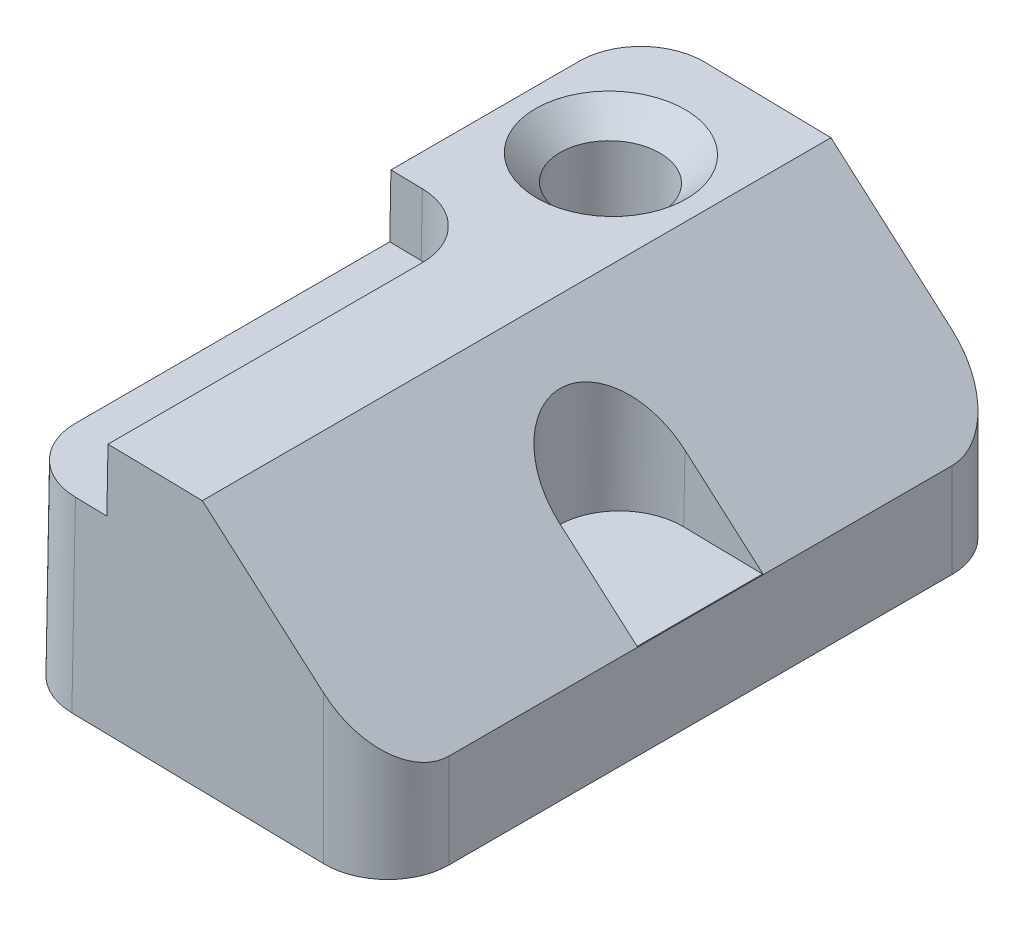
SolidWorks part; units mm, degrees
material "Plain Carbon Steel"
ref_plane "Front Plane" through (0, 0, 0) normal (0, 0, 1) x (1, 0, 0)
ref_plane "Top Plane" through (0, 0, 0) normal (0, 1, 0) x (1, 0, 0)
ref_plane "Right Plane" through (0, 0, 0) normal (1, 0, 0) x (0, 0, -1)
sketch "Sketch1" plane through (0, 0, 0) normal (0, 0, 1) x (1, 0, 0)
  line L0 (0, 0) -> (0.9549, 50.8)
  line L1 (0.9549, 50.8) -> (39.0549, 50.0838)
  line L2 (39.0549, 50.0838) -> (76.2, 17.6177)
  line L3 (76.2, 17.6177) -> (76.2, -1.4323)
  line L4 (76.2, -1.4323) -> (0, 0)
  dimension "D1" = 38.1
  dimension "D2" = 19.05
  dimension "D3" = 76.2
  dimension "D4" = 50.8
extrude "Boss-Extrude1" add sketch "Sketch1" along normal blind 127
sketch "Sketch2" plane through (0.9549, 50.8, 0) normal (0.0188, 0.9998, 0) x (0.9998, -0.0188, 0)
  line L0 (38.1067, 0) -> (0, 0) construction
  line L1 (0, -127) -> (0, 0) construction
  circle A0 centre (19.05, -25.4) radius 10.16
  dimension "D1" = 20.32
  dimension "D2" = 25.4
  dimension "D3" = 19.05
extrude "Cut-Extrude1" cut sketch "Sketch2" against normal through all
chamfer "Chamfer1" distance 5.08 angle 45 1 edges at (9.8433, 50.6329, 25.4)
sketch "Sketch3" plane through (0.9549, 50.8, 0) normal (0.0188, 0.9998, 0) x (0.9998, -0.0188, 0)
  line L1 (0, -127) -> (19.05, -127)
  line L2 (0, -127) -> (0, -50.8)
  line L3 (0, -50.8) -> (19.05, -50.8)
  line L4 (19.05, -127) -> (19.05, -50.8)
  dimension "D1" = 19.05
  dimension "D2" = 76.2
extrude "Cut-Extrude2" cut sketch "Sketch3" against normal blind 12.7
fillet "Fillet1" radius 12.7 1 edges at (19.8822, 44.0931, 50.8)
sketch "Sketch9" plane through (41.7308, 47.745, 0) normal (0.6581, 0.7529, 0) x (0.7529, -0.6581, 0)
  line L0 (45.7797, -63.5) -> (-76.9383, -63.5) construction
  line L1 (45.7797, -127) -> (45.7797, 0) construction
  point P4 (0, 0)
sketch "Sketch10" plane through (0.9549, 50.8, 0) normal (0.0188, 0.9998, 0) x (0.9998, -0.0188, 0)
  line L0 (75.7554, -50.8) -> (59.7534, -50.8)
  line L1 (59.7534, -76.2) -> (75.7554, -76.2)
  line L2 (75.7554, -76.2) -> (75.7554, -50.8)
  line L3 (75.8554, -63.5) -> (-18.0449, -63.5) construction
  arc A0 (59.7534, -50.8) -> (59.7534, -76.2) centre (59.7534, -63.5) ccw
  point P4 (0, 0)
  dimension "D2" = 12.7
  dimension "D1" = 16.002
extrude "Cut-Extrude4" cut sketch "Sketch10" against normal up to vertex (31.7623 mm away) contours L2 L0 A0 L1
fillet "Fillet2" radius 12.7 1 edges at (76.2, 8.0927, 127)
fillet "Fillet3" radius 12.7 1 edges at (0.3581, 19.0511, 127)
fillet "Fillet4" radius 12.7 1 edges at (0.4774, 25.4, 0)
fillet "Fillet5" radius 12.7 1 edges at (76.2, 8.0927, 0)
